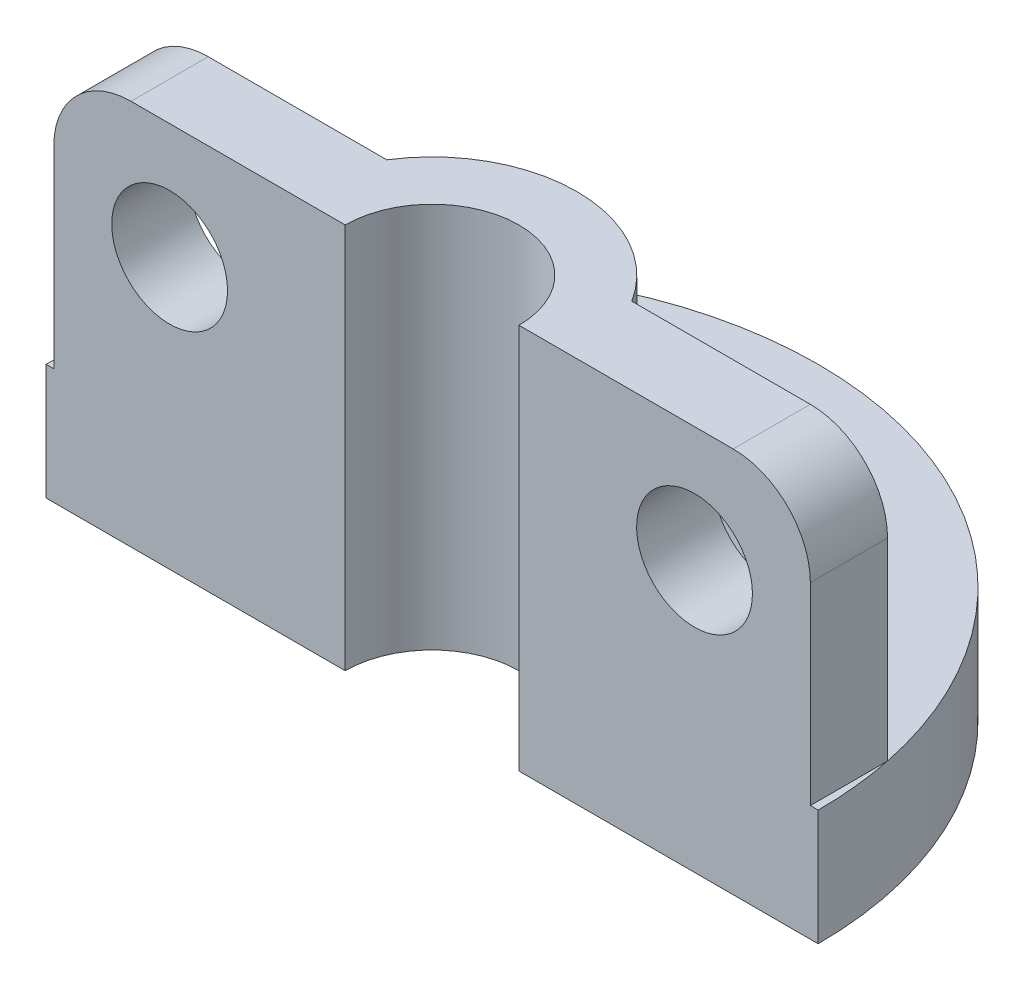
SolidWorks part; units mm, degrees
ref_plane "Front Plane" through (0, 0, 0) normal (0, 0, 1) x (1, 0, 0)
ref_plane "Top Plane" through (0, 0, 0) normal (0, 1, 0) x (1, 0, 0)
ref_plane "Right Plane" through (0, 0, 0) normal (1, 0, 0) x (0, 0, -1)
sketch "Sketch1" plane through (0, 0, 0) normal (0, 0, 1) x (1, 0, 0)
  line L0 (2.25, 0) -> (2.25, 10)
  line L1 (2.25, 10) -> (3.75, 10)
  line L2 (3.75, 10) -> (3.75, 3)
  line L3 (3.75, 3) -> (10, 3)
  line L4 (10, 3) -> (10, 0)
  line L5 (10, 0) -> (2.25, 0)
  line L6 (0, -739.1055) -> (0, 36216.1681) construction
  dimension "D1" = 10
  dimension "D2" = 2.25
  dimension "D3" = 10
  dimension "D4" = 3
  dimension "D5" = 1.5
revolve "Revolve1" add sketch "Sketch1" angle 360 about L6
fillet "Fillet1" radius 3 1 edges at (3.75, 3, 0)
sketch "Sketch3" plane through (0, 3, 0) normal (0, 1, 0) x (1, 0, 0)
  line L1 (-3.1721, -2) -> (-9.798, -2)
  line L2 (-3.1721, -2) -> (-3.1721, 2)
  line L3 (-3.1721, 2) -> (-9.798, 2)
  line L4 (-9.798, -2) -> (-9.798, 2)
  circle A0 centre (0, 0) radius 3.75 construction
  circle A1 centre (0, 0) radius 10 construction
  point P8 (-3.1721, 0)
  dimension "D1" = 4
extrude "Boss-Extrude1" add sketch "Sketch3" along normal up to surface (7 mm away) up to face at (2.25, 10, 0)
mirror "Mirror1" about plane through (0, 0, 0) normal (1, 0, 0) of "Boss-Extrude1"
sketch "Sketch2" plane through (0, 0, 0) normal (0, 1, 0) x (1, 0, 0)
  line L1 (-15, -15) -> (15, -15)
  line L2 (-15, -15) -> (-15, 0)
  line L3 (-15, 0) -> (15, 0)
  line L4 (15, -15) -> (15, 0)
  point P4 (0, 0)
  dimension "D1" = 30
  dimension "D2" = 15
extrude "Cut-Extrude1" cut sketch "Sketch2" along normal through all
hole_wizard "Ø3.0mm Dowel Hole1" positions "Sketch6" profile "Sketch7" hole size "Ø3.0" standard "ANSI Metric" end condition up to next
sketch "Sketch6" plane through (0, 0, -2) normal (0, 0, -1) x (-1, 0, 0)
  line L0 (-9.798, 10) -> (-9.798, 3) construction
  line L1 (9.798, 10) -> (9.798, 3) construction
  line L2 (-3.1721, 10) -> (-9.798, 10) construction
  line L3 (3.1721, 10) -> (9.798, 10) construction
  point P0 (6.798, 7)
  point P2 (-6.798, 7)
  dimension "D1" = 3
  dimension "D2" = 3
  dimension "D3" = 3
  dimension "D4" = 3
sketch "Sketch7" plane through (-6.798, 7, -2) normal (1, 0, 0) x (0, 1, 0)
  line L0 (0, 0) -> (0, 2)
  line L1 (0, 2) -> (1.5, 2)
  line L2 (1.5, 2) -> (1.5, 0)
  line L5 (1.5, 0) -> (0, 0)
  line L11 (0, -6.35) -> (0, 107.95) construction
  dimension "Thru Hole Dia." = 3
  dimension "Thru Hole Depth" = 2
fillet "Fillet2" radius 2 2 edges at (-9.798, 10, -1) (9.798, 10, -1)
